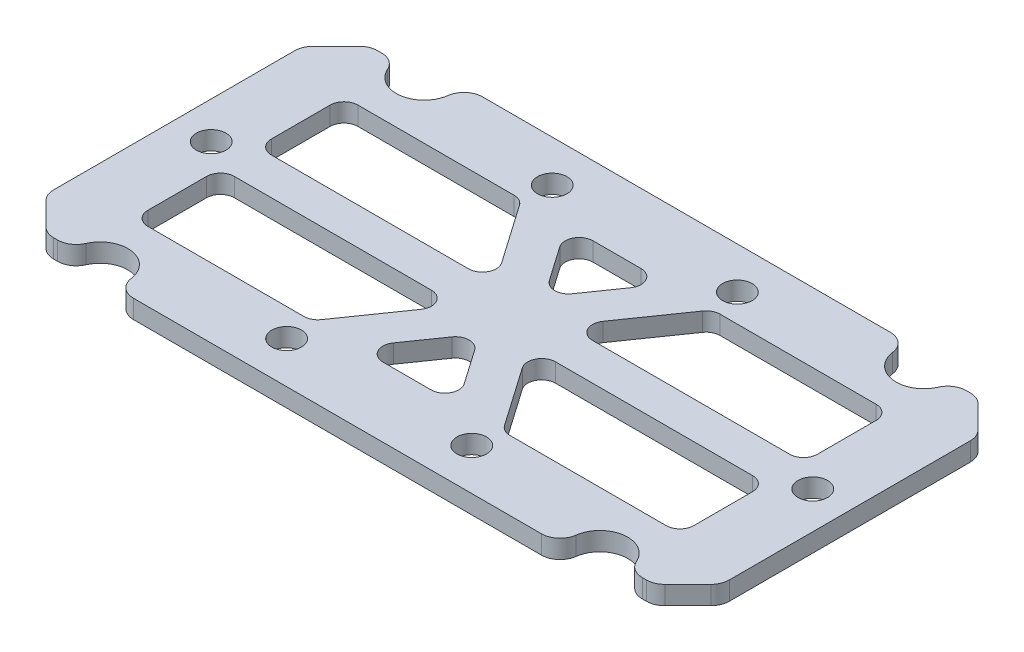
SolidWorks part; units mm, degrees
material "Thornel Mat VMA"
ref_plane "前视基准面" through (0, 0, 0) normal (0, 0, 1) x (1, 0, 0)
ref_plane "上视基准面" through (0, 0, 0) normal (0, 1, 0) x (1, 0, 0)
ref_plane "右视基准面" through (0, 0, 0) normal (1, 0, 0) x (0, 0, -1)
other "Configuration Table"
sketch "草图1" plane through (0, 0, 0) normal (0, 1, 0) x (1, 0, 0)
  line L1 (-10, 14.35) -> (10, 14.35) construction
  line L2 (-10, 14.35) -> (-10, -14.35) construction
  line L3 (-10, -14.35) -> (10, -14.35) construction
  line L4 (10, 14.35) -> (10, -14.35) construction
  line L5 (-10, 14.35) -> (10, -14.35) construction
  line L6 (-10, -14.35) -> (10, 14.35) construction
  line L7 (-36.5, 18.85) -> (36.5, 18.85)
  line L8 (-36.5, 18.85) -> (-36.5, -18.85)
  line L9 (-36.5, -18.85) -> (36.5, -18.85)
  line L10 (36.5, 18.85) -> (36.5, -18.85)
  line L11 (-36.5, 18.85) -> (36.5, -18.85) construction
  line L12 (-36.5, -18.85) -> (36.5, 18.85) construction
  circle A0 centre (10, -14.35) radius 1.6
  circle A1 centre (-10, -14.35) radius 1.6
  circle A2 centre (-10, 14.35) radius 1.6
  circle A3 centre (10, 14.35) radius 1.6
  circle A4 centre (-32.5, 0) radius 1.6
  circle A5 centre (32.5, 0) radius 1.6
  point P0 (0, 0)
  point P10 (0, 0)
  dimension "D3" = 3.2
  dimension "D1" = 20
  dimension "D2" = 28.7
  dimension "D4" = 4.5
  dimension "D5" = 65
  dimension "D6" = 32.5
  dimension "D7" = 4
extrude "凸台-拉伸1" add sketch "草图1" along normal blind 2
sketch "草图2" plane through (0, 2, 0) normal (0, 1, 0) x (1, 0, 0)
  line L1 (-29.5, 11.35) -> (29.5, 11.35)
  line L2 (-29.5, 11.35) -> (-29.5, -11.35)
  line L3 (-29.5, -11.35) -> (29.5, -11.35)
  line L4 (29.5, 11.35) -> (29.5, -11.35)
  line L5 (-29.5, 11.35) -> (29.5, -11.35) construction
  line L6 (-29.5, -11.35) -> (29.5, 11.35) construction
  circle A0 centre (10, -14.35) radius 1.6 construction
  circle A1 centre (32.5, 0) radius 1.6 construction
  point P0 (0, 0)
  dimension "D1" = 3
  dimension "D2" = 3
extrude "切除-拉伸1" cut sketch "草图2" against normal blind 10
sketch "草图3" plane through (0, 2, 0) normal (0, 1, 0) x (1, 0, 0)
  line L0 (-29.5, 0) -> (29.5, 0)
  line L1 (-29.5, 11.35) -> (-29.5, -11.35) construction
  line L2 (29.5, -11.35) -> (29.5, 11.35) construction
  line L3 (-10, 14.35) -> (10, -14.35)
  line L4 (10, 14.35) -> (-10, -14.35)
extrude "拉伸-薄壁1" add sketch "草图3" against normal blind 2 thin thin type mid plane wall 4
sketch "草图4" plane through (0, 2, 0) normal (0, 1, 0) x (1, 0, 0)
  line L0 (11.3127, -13.4352) -> (8.6873, -15.2648) construction
  line L1 (-8.6873, -15.2648) -> (-11.3127, -13.4352) construction
  line L2 (8.6873, 15.2648) -> (11.3127, 13.4352) construction
  line L3 (-11.3127, 13.4352) -> (-8.6873, 15.2648) construction
  circle A0 centre (10, -14.35) radius 1.6
  circle A1 centre (-10, -14.35) radius 1.6
  circle A2 centre (10, 14.35) radius 1.6
  circle A3 centre (-10, 14.35) radius 1.6
  dimension "D1" = 3.2
extrude "切除-拉伸2" cut sketch "草图4" against normal blind 2
fillet "圆角2" radius 1.5 22 edges at (29.5, 1, 11.35) (10.3471, 1, 11.35) (3.8314, 1, 2) (29.5, 1, 2) (-29.5, 1, 11.35) (-29.5, 1, 2) (-3.8314, 1, 2) (-10.3471, 1, 11.35) (-5.4717, 1, 11.35) (0, 1, 3.4981) (5.4717, 1, 11.35) (-3.8314, 1, -2) (-29.5, 1, -2) (-10.3471, 1, -11.35) (29.5, 1, -11.35) (29.5, 1, -2) (3.8314, 1, -2) (10.3471, 1, -11.35) (5.4717, 1, -11.35) (0, 1, -3.4981) (-5.4717, 1, -11.35) (-29.5, 1, -11.35)
chamfer "倒角1" distance 5 angle 45 4 edges at (36.5, 1, -18.85) (-36.5, 1, -18.85) (-36.5, 1, 18.85) (36.5, 1, 18.85)
sketch "草图6" plane through (0, 2, 0) normal (0, 1, 0) x (1, 0, 0)
  circle A0 centre (27, 17.5) radius 3
  circle A1 centre (27, -17.5) radius 3
  circle A2 centre (-27, -17.5) radius 3
  circle A3 centre (-27, 17.5) radius 3
  dimension "D1" = 6
extrude "切除-拉伸3" cut sketch "草图6" against normal blind 10
sketch "草图7" plane through (0, 2, 0) normal (0, 1, 0) x (1, 0, 0)
  line L0 (30, -17.5) -> (32.85, -17.5)
  line L1 (31.5, -18.85) -> (36.5, -13.85) construction
  line L2 (24, -17.5) -> (24, -18.85)
  line L3 (-24.3209, -18.85) -> (24.3209, -18.85) construction
  line L4 (29.6791, -18.85) -> (31.5, -18.85)
  line L5 (31.5, -18.85) -> (32.85, -17.5)
  line L6 (24.3209, -18.85) -> (24, -18.85)
  line L7 (0, -25.2844) -> (0, 22.1432) construction
  line L8 (0, 0) -> (43.4341, 0) construction
  line L9 (24.3209, 18.85) -> (24, 18.85)
  line L10 (31.5, 18.85) -> (32.85, 17.5)
  line L11 (29.6791, 18.85) -> (31.5, 18.85)
  line L12 (24, 17.5) -> (24, 18.85)
  line L13 (30, 17.5) -> (32.85, 17.5)
  line L14 (-30, 17.5) -> (-32.85, 17.5)
  line L15 (-24, 17.5) -> (-24, 18.85)
  line L16 (-29.6791, 18.85) -> (-31.5, 18.85)
  line L17 (-31.5, 18.85) -> (-32.85, 17.5)
  line L18 (-24.3209, 18.85) -> (-24, 18.85)
  line L19 (-24.3209, -18.85) -> (-24, -18.85)
  line L20 (-31.5, -18.85) -> (-32.85, -17.5)
  line L21 (-29.6791, -18.85) -> (-31.5, -18.85)
  line L22 (-24, -17.5) -> (-24, -18.85)
  line L23 (-30, -17.5) -> (-32.85, -17.5)
  arc A0 (29.6791, -18.85) -> (24.3209, -18.85) centre (27, -17.5) ccw construction
  arc A1 (29.6791, -18.85) -> (30, -17.5) centre (27, -17.5) ccw
  arc A2 (24, -17.5) -> (24.3209, -18.85) centre (27, -17.5) ccw
  arc A3 (24, 17.5) -> (24.3209, 18.85) centre (27, 17.5) cw
  arc A4 (29.6791, 18.85) -> (30, 17.5) centre (27, 17.5) cw
  arc A5 (-29.6791, 18.85) -> (-30, 17.5) centre (-27, 17.5) ccw
  arc A6 (-24, 17.5) -> (-24.3209, 18.85) centre (-27, 17.5) ccw
  arc A7 (-24, -17.5) -> (-24.3209, -18.85) centre (-27, -17.5) cw
  arc A8 (-29.6791, -18.85) -> (-30, -17.5) centre (-27, -17.5) cw
extrude "切除-拉伸4" cut sketch "草图7" against normal blind 10
fillet "圆角3" radius 2 16 edges at (-36.5, 1, -13.85) (-36.5, 1, 13.85) (36.5, 1, 13.85) (36.5, 1, -13.85) (-32.85, 1, 17.5) (-30, 1, 17.5) (24, 1, 18.85) (30, 1, 17.5) (32.85, 1, 17.5) (32.85, 1, -17.5) (30, 1, -17.5) (24, 1, -18.85) (-24, 1, -18.85) (-30, 1, -17.5) (-32.85, 1, -17.5) (-24, 1, 18.85)
